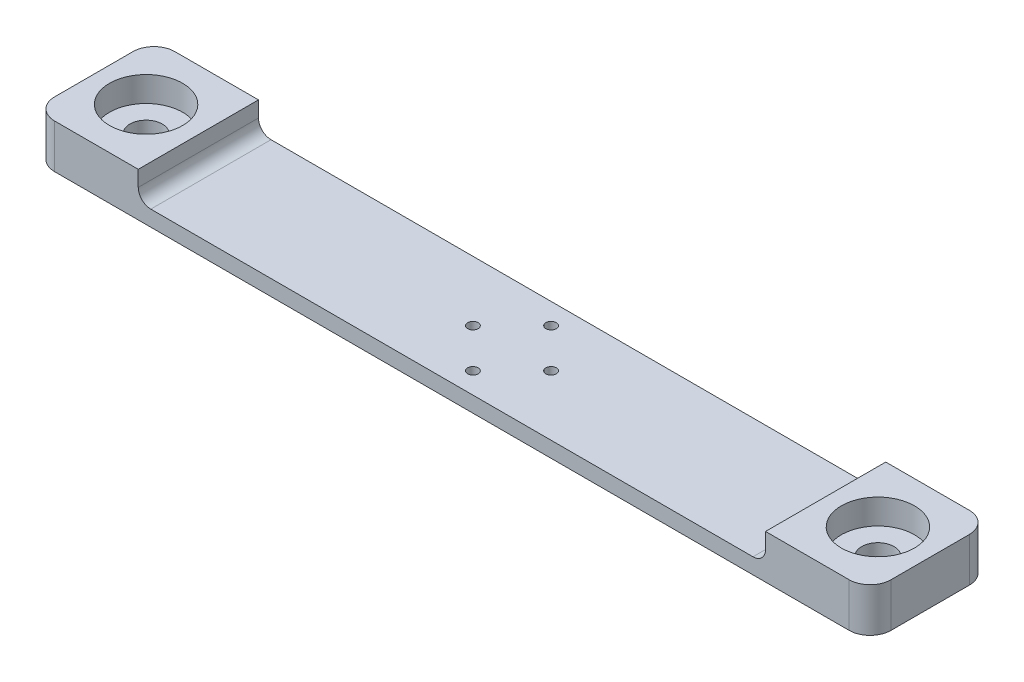
SolidWorks part; units mm, degrees
ref_plane "Front Plane" through (0, 0, 0) normal (0, 0, 1) x (1, 0, 0)
ref_plane "Top Plane" through (0, 0, 0) normal (0, 1, 0) x (1, 0, 0)
ref_plane "Right Plane" through (0, 0, 0) normal (1, 0, 0) x (0, 0, -1)
sketch "Sketch1" plane through (0, 0, 0) normal (0, 1, 0) x (1, 0, 0)
  line L0 (0, 0) -> (0, 4.9523) construction
  line L1 (0, 4.9523) -> (0, 0) construction
  line L2 (0, 0) -> (2.8355, 0) construction
  circle A0 centre (0, 0) radius 13.97
  circle A2 centre (0, 9.5) radius 1.275
  circle A3 centre (9.5, 0) radius 1.275
  circle A4 centre (0, -9.5) radius 1.275
  circle A5 centre (-9.5, 0) radius 1.275
  dimension "D2" = 27.94
  dimension "D3" = 2.55
extrude "Boss-Extrude1" add sketch "Sketch1" along normal blind 3.048
sketch "Sketch2" plane through (0, 3.048, 0) normal (0, 1, 0) x (1, 0, 0)
  line L1 (-96.52, -14.605) -> (96.52, -14.605)
  line L2 (-101.6, -9.525) -> (-101.6, 9.525)
  line L3 (-96.52, 14.605) -> (96.52, 14.605)
  line L4 (101.6, -9.525) -> (101.6, 9.525)
  line L5 (-101.6, -14.605) -> (101.6, 14.605) construction
  line L6 (-101.6, 14.605) -> (101.6, -14.605) construction
  circle A0 centre (-88.9, 0) radius 8.89
  circle A1 centre (88.9, 0) radius 8.89
  arc A3 (96.52, 14.605) -> (101.6, 9.525) centre (96.52, 9.525) cw
  arc A4 (96.52, -14.605) -> (101.6, -9.525) centre (96.52, -9.525) ccw
  arc A5 (-96.52, -14.605) -> (-101.6, -9.525) centre (-96.52, -9.525) cw
  arc A6 (-101.6, 9.525) -> (-96.52, 14.605) centre (-96.52, 9.525) cw
  circle A7 centre (9.5, 0) radius 1.275 construction
  circle A8 centre (0, 9.5) radius 1.275 construction
  circle A9 centre (-9.5, 0) radius 1.275 construction
  circle A10 centre (0, -9.5) radius 1.275 construction
  circle A11 centre (9.5, 0) radius 1.275
  circle A12 centre (0, 9.5) radius 1.275
  circle A13 centre (-9.5, 0) radius 1.275
  circle A14 centre (0, -9.5) radius 1.275
  point P0 (0, 0)
  point P12 (-198.3194, 52.0905)
  dimension "D2" = 17.78
  dimension "D3" = 17.78
  dimension "D8" = 5.08
  dimension "D1" = 29.21
  dimension "D4" = 88.9
  dimension "D6" = 12.7
  dimension "D7" = 12.7
extrude "Boss-Extrude2" add sketch "Sketch2" along normal blind 7.62 and the other way through all
sketch "Sketch5" plane through (0, 0, -14.605) normal (0, 0, -1) x (-1, 0, 0)
  line L0 (-101.6, 0) -> (-101.6, 10.668)
  line L1 (-101.6, 10.668) -> (-76.2, 10.668)
  line L2 (-96.52, 10.668) -> (96.52, 10.668) construction
  line L3 (-76.2, 10.668) -> (-76.2, 3.81)
  line L4 (-76.2, 3.81) -> (76.2, 3.81)
  line L5 (0, 3.81) -> (0, 0)
  line L6 (101.6, 0) -> (-101.6, 0)
  line L7 (76.2, 10.668) -> (76.2, 3.81)
  line L8 (101.6, 10.668) -> (76.2, 10.668)
  line L9 (101.6, 0) -> (101.6, 10.668)
  line M8 (96.52, 10.668) -> (-96.52, 10.668)
  dimension "D1" = 25.4
  dimension "D2" = 3.81
extrude "Cut-Extrude2" cut sketch "Sketch5" against normal through all contours L7 L3 L4 M8
sketch "Sketch6" plane through (0, 0, 0) normal (0, -1, 0) x (1, 0, 0)
  circle A0 centre (-88.9, 0) radius 8.89
  circle A1 centre (-88.9, 0) radius 3.937
  circle A2 centre (88.9, 0) radius 8.89
  circle A3 centre (88.9, 0) radius 3.937
  dimension "D1" = 7.874
  dimension "D2" = 7.874
extrude "Boss-Extrude3" add sketch "Sketch6" against normal blind 4.572
fillet "Fillet2" radius 3.048 2 edges at (76.2, 3.81, 0) (-76.2, 3.81, 0)
